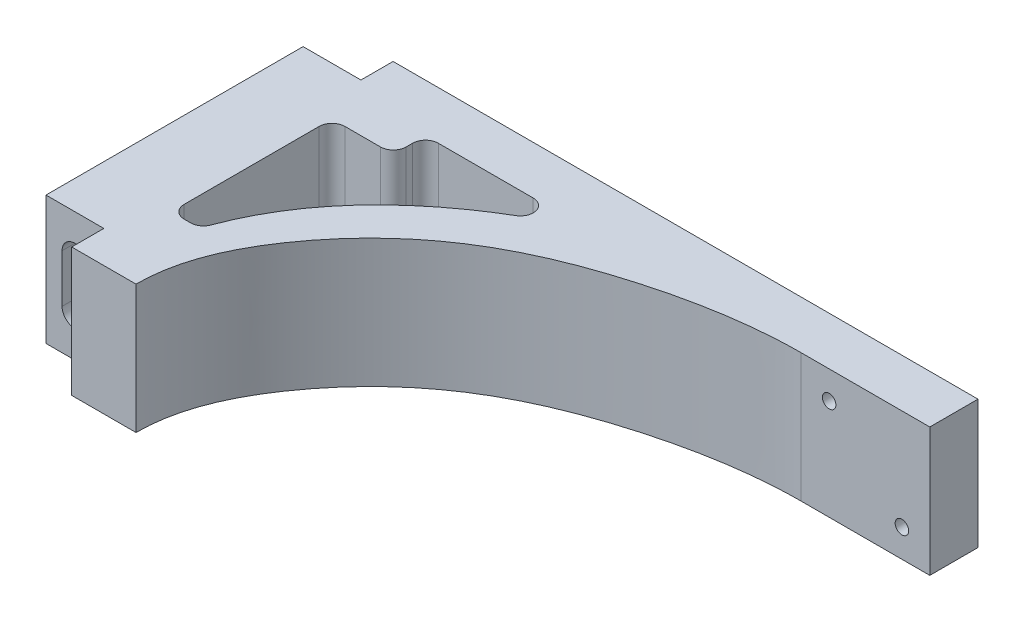
SolidWorks part; units mm, degrees
ref_plane "Front Plane" through (0, 0, 0) normal (0, 0, 1) x (1, 0, 0)
ref_plane "Top Plane" through (0, 0, 0) normal (0, 1, 0) x (1, 0, 0)
ref_plane "Right Plane" through (0, 0, 0) normal (1, 0, 0) x (0, 0, -1)
sketch "Sketch2" plane through (0, 0, 0) normal (0, 1, 0) x (1, 0, 0)
  line L0 (-28.6583, 0.7462) -> (-28.6583, -39.2538)
  line L1 (-28.6583, 0.7462) -> (-19.6583, 0.7462)
  line L2 (-19.6583, 0.7462) -> (-19.6583, 5.7462)
  line L3 (-19.6583, 5.7462) -> (71.3417, 5.7462)
  line L4 (71.3417, 5.7462) -> (71.3417, -1.7538)
  line L7 (-9.6583, -44.2538) -> (-19.6583, -44.2538)
  line L8 (-19.6583, -44.2538) -> (-19.6583, -39.2538)
  line L9 (-19.6583, -39.2538) -> (-28.6583, -39.2538)
  line L10 (71.3417, -1.7538) -> (51.3417, -1.7538)
  line L11 (49.908, -1.7538) -> (62.8078, -1.7538) construction
  line L12 (-9.6583, -49.0984) -> (-9.6583, -39.4092) construction
  line L13 (-16.6583, -8.7538) -> (-16.6583, -29.7538)
  line L14 (-13.6583, -31.7538) -> (-14.6583, -31.7538)
  line L19 (-5.1206, -1.7538) -> (9.6466, -1.7538)
  line L20 (-7.1206, -4.7538) -> (-7.1206, -3.7538)
  line L21 (-14.6583, -6.7538) -> (-9.1206, -6.7538)
  arc A0 (10.6589, -5.4787) -> (9.6466, -1.7538) centre (9.6466, -3.7538) ccw
  arc A1 (-7.1206, -3.7538) -> (-5.1206, -1.7538) centre (-5.1206, -3.7538) cw
  arc A2 (-7.1206, -4.7538) -> (-9.1206, -6.7538) centre (-9.1206, -4.7538) cw
  arc A3 (-16.6583, -8.7538) -> (-14.6583, -6.7538) centre (-14.6583, -8.7538) cw
  arc A4 (-13.6583, -31.7538) -> (-11.7838, -30.4512) centre (-13.6583, -29.7538) ccw
  arc A5 (-16.6583, -29.7538) -> (-14.6583, -31.7538) centre (-14.6583, -29.7538) ccw
  spline S0 degree 3 poles (51.3417, -1.7538) (43.9502, -1.7538) (29.0668, -4.2859) (9.2944, -12.3277) (-4.6758, -26.6259) (-9.6583, -37.8885) (-9.6583, -44.2538) knots 0 0 0 0 0.278288 0.54895 0.780652 1 1 1 1
  spline S2 degree 3 poles (-11.7838, -30.4512) (-11.2742, -29.0814) (-9.9243, -25.9699) (-6.2527, -19.7527) (0.0011, -12.8231) (6.3671, -8.0794) (10.0087, -5.8603) (10.6589, -5.4787) knots 0.45705 0.45705 0.45705 0.45705 0.498596 0.553238 0.662523 0.771807 0.795347 0.795347 0.795347 0.795347
  point P11 (-3.9258, -27.4846)
  point P18 (9.1783, -14.1158)
  point P19 (29.1118, -5.1236)
  point P30 (0, 0)
  dimension "D9" = 2
  dimension "D10" = 2
  dimension "D11" = 1
  dimension "D1" = 40
  dimension "D2" = 9
  dimension "D3" = 5
  dimension "D4" = 5
  dimension "D5" = 100
  dimension "D6" = 10
  dimension "D7" = 20
  dimension "D8" = 7.5
  dimension "D12" = 12
extrude "Boss-Extrude1" add sketch "Sketch2" along normal blind 20 contours L0 L9 L8 L7 S0 L10 L4 L3 L2 L1
sketch "Sketch3" plane through (0, 0, -5.7462) normal (0, 0, -1) x (-1, 0, 0)
  line L0 (-71.3417, 20) -> (-71.3417, 0) construction
  line L1 (-66.9986, 4.3431) -> (-61.3417, 10) construction
  line L2 (-61.3417, 10) -> (-55.6849, 15.6569) construction
  line L3 (-61.3417, 10) -> (-65.0251, 10) construction
  circle A0 centre (-61.3417, 10) radius 3.6834 construction
  circle A1 centre (-66.9986, 4.3431) radius 1.05
  circle A2 centre (-55.6849, 15.6569) radius 1.05
  dimension "D2" = 45
  dimension "D4" = 2.1
  dimension "D5" = 2.1
  dimension "D6" = 16
  dimension "D1" = 10
  dimension "D3" = 8
extrude "Cut-Extrude1" cut sketch "Sketch3" against normal blind 20 contours A2 | A1
sketch "Sketch4" plane through (0, 0, -0.7462) normal (0, 0, -1) x (-1, 0, 0)
  line L0 (24.1583, 6.25) -> (24.1583, 13.75) construction
  line L1 (22.1583, 6.25) -> (22.1583, 13.75)
  line L2 (26.1583, 6.25) -> (26.1583, 13.75)
  line L3 (24.1583, 10) -> (28.6583, 10) construction
  line L4 (28.6583, 20) -> (28.6583, 0) construction
  line L8 (19.6583, 20) -> (19.6583, 0) construction
  arc A0 (22.1583, 6.25) -> (26.1583, 6.25) centre (24.1583, 6.25) ccw
  arc A1 (26.1583, 13.75) -> (22.1583, 13.75) centre (24.1583, 13.75) ccw
  point P2 (24.1583, 10)
  point P11 (0, 0)
  dimension "D2" = 2
  dimension "D1" = 7.5
  dimension "D3" = 2.5
extrude "Cut-Extrude2" cut sketch "Sketch4" against normal up to surface (40 mm away) contours L2 A1 L1 A0 up to face at (-24.1583, 10, 39.2538)
